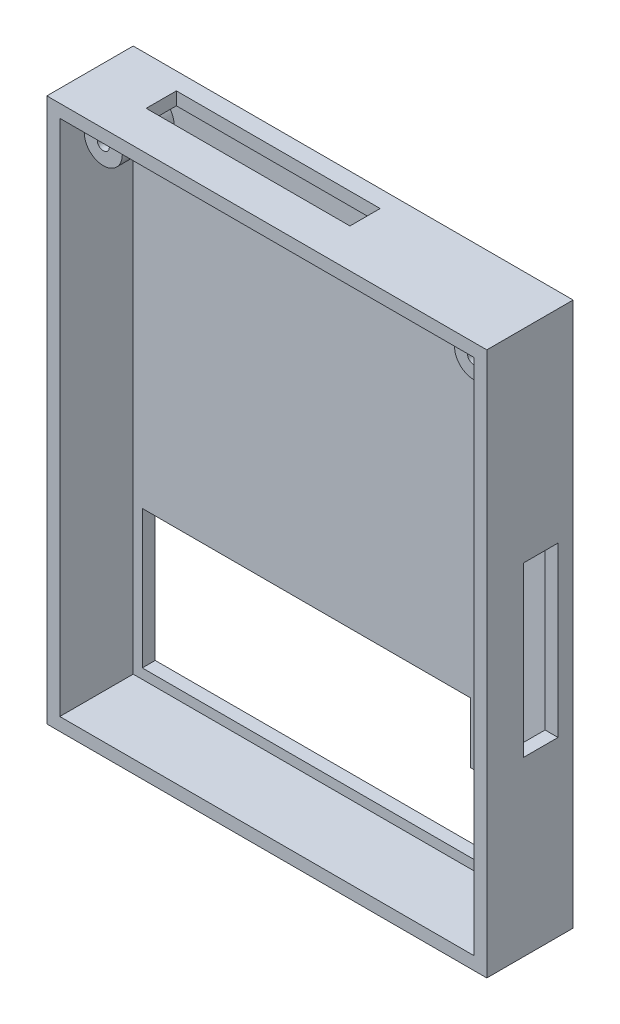
SolidWorks part; units mm, degrees
ref_plane "Alzado" through (0, 0, 0) normal (0, 0, 1) x (1, 0, 0)
ref_plane "Planta" through (0, 0, 0) normal (0, 1, 0) x (1, 0, 0)
ref_plane "Vista lateral" through (0, 0, 0) normal (1, 0, 0) x (0, 0, -1)
sketch "Croquis1" plane through (0, 0, 0) normal (0, 0, 1) x (1, 0, 0)
  line L1 (0, 0) -> (101.9, 0)
  line L2 (0, 0) -> (0, 126)
  line L3 (0, 126) -> (101.9, 126)
  line L4 (101.9, 0) -> (101.9, 126)
  dimension "D1" = 126
  dimension "D2" = 101.9
extrude "Saliente-Extruir1" add sketch "Croquis1" along normal blind 15
shell "Vaciado1" thickness 3
sketch "Croquis2" plane through (0, 0, 3) normal (0, 0, 1) x (1, 0, 0)
  line L0 (3, 123) -> (3, 3) construction
  line L1 (5.1, 37.3) -> (81.1, 37.3)
  line L2 (5.1, 37.3) -> (5.1, 5.3)
  line L3 (5.1, 5.3) -> (97.1, 5.3)
  line L4 (97.1, 23.3) -> (97.1, 5.3)
  line L5 (3, 3) -> (98.9, 3) construction
  line L9 (81.1, 37.3) -> (81.1, 23.3)
  line L10 (81.1, 23.3) -> (97.1, 23.3)
  dimension "D1" = 2.1
  dimension "D2" = 2.3
  dimension "D3" = 32
  dimension "D4" = 92
  dimension "D5" = 14
  dimension "D6" = 16
extrude "Cortar-Extruir1" cut sketch "Croquis2" against normal blind 15
sketch "Croquis3" plane through (101.9, 0, 0) normal (1, 0, 0) x (0, 0, -1)
  line L0 (-15, 0) -> (0, 0) construction
  line L1 (-11.5, 79) -> (-3.5, 79)
  line L2 (-11.5, 79) -> (-11.5, 40)
  line L3 (-11.5, 40) -> (-3.5, 40)
  line L4 (-3.5, 79) -> (-3.5, 40)
  line L5 (-15, 126) -> (0, 126) construction
  point P8 (-7.5, 79)
  point P9 (-7.5, 126)
  dimension "D1" = 40
  dimension "D2" = 47
  dimension "D3" = 8
extrude "Cortar-Extruir2" cut sketch "Croquis3" against normal blind 15
sketch "Croquis4" plane through (0, 126, 0) normal (0, 1, 0) x (1, 0, 0)
  line L0 (0, -15) -> (0, 0) construction
  line L1 (14, -4) -> (61.2, -4)
  line L2 (14, -4) -> (14, -11)
  line L3 (14, -11) -> (61.2, -11)
  line L4 (61.2, -4) -> (61.2, -11)
  line L5 (101.9, -15) -> (101.9, 0) construction
  point P8 (14, -7.5)
  point P9 (0, -7.5)
  dimension "D1" = 14
  dimension "D2" = 40.7
  dimension "D3" = 7
extrude "Cortar-Extruir3" cut sketch "Croquis4" against normal blind 15
sketch "Croquis5" plane through (0, 0, 3) normal (0, 0, 1) x (1, 0, 0)
  line L0 (3, 123) -> (3, 3) construction
  line L1 (98.9, 123) -> (3, 123) construction
  line L2 (98.9, 3) -> (98.9, 123) construction
  circle A0 centre (8.07, 117.93) radius 1.77 construction
  circle A1 centre (93.83, 117.93) radius 1.77 construction
  circle A2 centre (8.07, 117.93) radius 1.4
  circle A3 centre (93.83, 117.93) radius 1.4
  point P4 (8.07, 119.7)
  point P5 (6.3, 117.93)
  point P7 (95.6, 117.93)
  dimension "D1" = 3.54
  dimension "D5" = 2.8
  dimension "D2" = 3.3
  dimension "D3" = 3.3
  dimension "D4" = 3.3
extrude "Cortar-Extruir4" cut sketch "Croquis5" against normal blind 15
sketch "Croquis6" plane through (0, 0, 3) normal (0, 0, 1) x (1, 0, 0)
  circle A0 centre (93.83, 117.93) radius 1.4 construction
  circle A1 centre (8.07, 117.93) radius 1.4 construction
  circle A2 centre (93.83, 117.93) radius 1.4
  circle A3 centre (8.07, 117.93) radius 1.4
  circle A4 centre (93.83, 117.93) radius 4.4
  circle A5 centre (8.07, 117.93) radius 4.4
  dimension "D1" = 3
extrude "Saliente-Extruir2" add sketch "Croquis6" along normal blind 12
sketch "Croquis7" plane through (0, 0, 15) normal (0, 0, 1) x (1, 0, 0)
  line L0 (3, 123) -> (3, 3)
  line L1 (3, 3) -> (98.9, 3)
  line L2 (98.9, 3) -> (98.9, 123)
  line L3 (98.9, 123) -> (3, 123)
  line L4 (0, 126) -> (0, 0)
  line L5 (0, 0) -> (101.9, 0)
  line L6 (101.9, 0) -> (101.9, 126)
  line L7 (101.9, 126) -> (0, 126)
  line L8 (0, 126) -> (0, 0)
  line L9 (0, 0) -> (101.9, 0)
  line L10 (101.9, 0) -> (101.9, 126)
  line L11 (101.9, 126) -> (0, 126)
  dimension "D1" = 0
  dimension "D2" = 3
extrude "Saliente-Extruir3" add sketch "Croquis7" along normal blind 5
